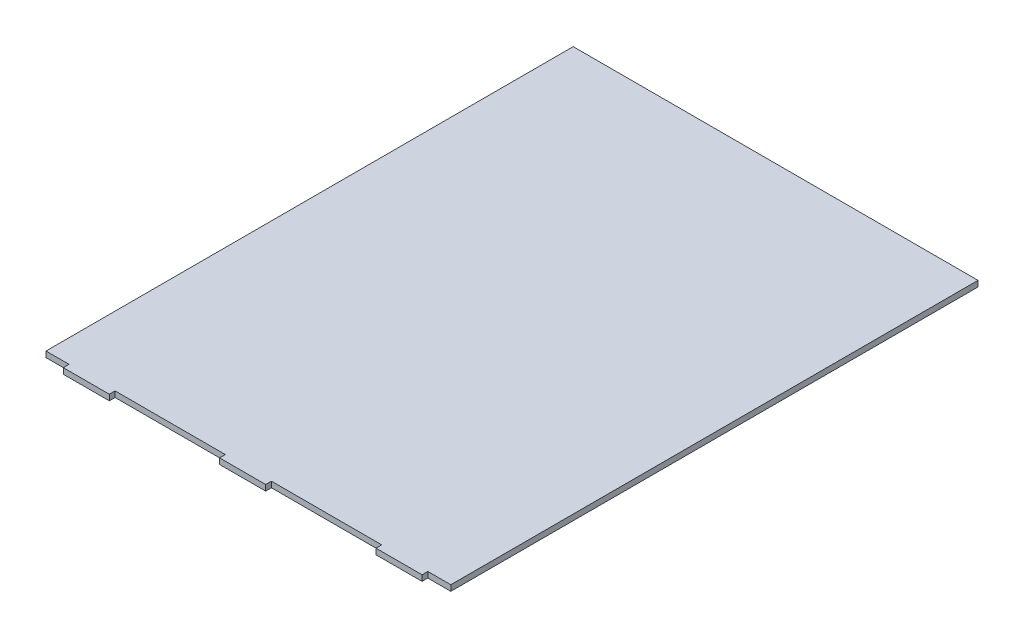
SolidWorks part; units mm, degrees
material "6061-T6 (SS)"
ref_plane "X-Y Datum" through (0, 0, 0) normal (0, 0, 1) x (1, 0, 0)
ref_plane "X-Z Datum" through (0, 0, 0) normal (0, 1, 0) x (1, 0, 0)
ref_plane "Y-Z Datum" through (0, 0, 0) normal (1, 0, 0) x (0, 0, -1)
sketch "Sketch1" plane through (0, 0, 0) normal (0, 1, 0) x (1, 0, 0)
  line L0 (0, 0) -> (0, -3.175) construction
  line L1 (0, 0) -> (12.7, 0)
  line L2 (0, 0) -> (0, 290.83)
  line L3 (0, 290.83) -> (223.3117, 290.83)
  line L4 (223.3117, 0) -> (223.3117, 290.83)
  line L5 (0, -3.175) -> (12.7, -3.175) construction
  line L6 (96.7224, 0) -> (98.9559, 0)
  line L7 (12.7, -3.175) -> (38.1, -3.175)
  line L8 (12.7, -3.175) -> (12.7, 0)
  line L10 (38.1, -3.175) -> (38.1, 0)
  line L15 (38.1, 0) -> (96.7224, 0)
  line L20 (38.1, -3.175) -> (185.2117, -3.175) construction
  line L21 (111.6559, -3.175) -> (111.6559, 0) construction
  line L22 (124.3559, 0) -> (180.7449, 0)
  line L23 (210.6117, 0) -> (223.3117, 0)
  line L24 (223.3117, -3.175) -> (210.6117, -3.175) construction
  line L25 (180.7449, 0) -> (185.2117, 0)
  line L27 (210.6117, -3.175) -> (185.2117, -3.175)
  line L28 (210.6117, -3.175) -> (210.6117, 0)
  line L30 (185.2117, -3.175) -> (185.2117, 0)
  line L36 (98.9559, 0) -> (98.9559, -3.175)
  line L37 (98.9559, -3.175) -> (124.3559, -3.175)
  line L38 (124.3559, 0) -> (124.3559, -3.175)
  line L39 (98.9559, 0) -> (124.3559, -3.175) construction
  line L40 (98.9559, -3.175) -> (124.3559, 0) construction
  point P16 (111.6559, -1.5875)
  point P18 (111.6559, -1.5875)
extrude "Boss-Extrude1" add sketch "Sketch1" along normal blind 3.175
